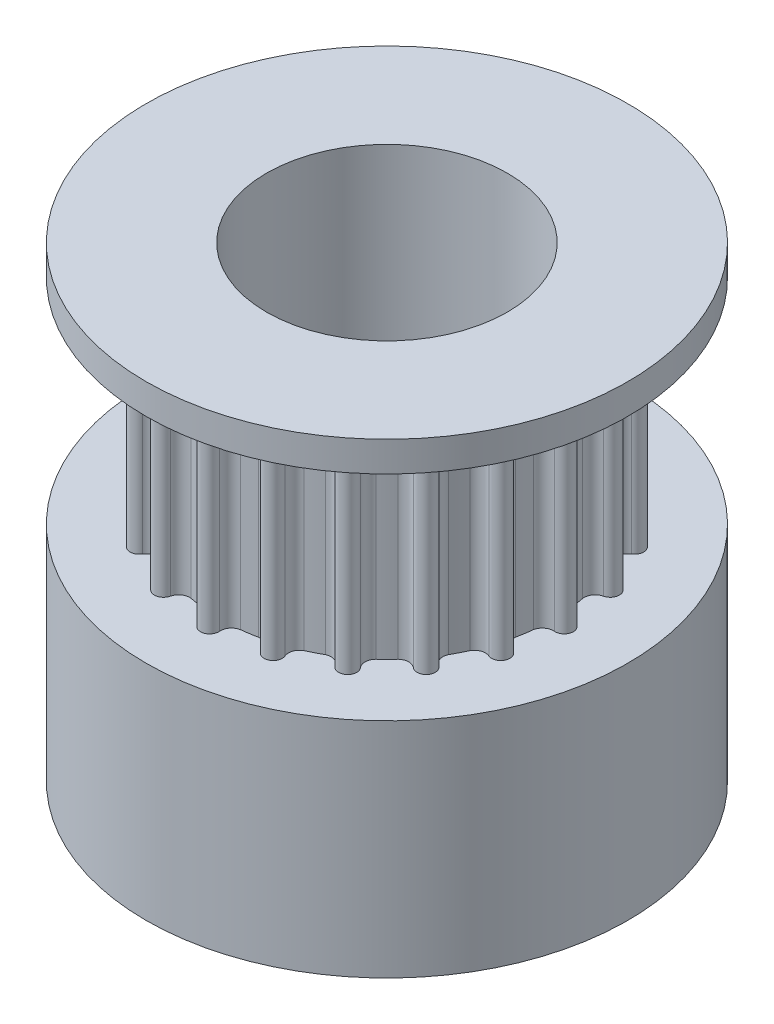
SolidWorks part; units mm, degrees
ref_plane "Front Plane" through (0, 0, 0) normal (0, 0, 1) x (1, 0, 0)
ref_plane "Top Plane" through (0, 0, 0) normal (0, 1, 0) x (1, 0, 0)
ref_plane "Right Plane" through (0, 0, 0) normal (1, 0, 0) x (0, 0, -1)
sketch "Sketch2" plane through (0, 0, 0) normal (0, 1, 0) x (1, 0, 0)
  circle A0 centre (0, 0) radius 8
  circle A1 centre (0, 0) radius 4
  dimension "D1" = 16
  dimension "D2" = 8
extrude "Boss-Extrude1" add sketch "Sketch2" along normal blind 15.5
sketch "Sketch3" plane through (0, 15.5, 0) normal (0, 1, 0) x (1, 0, 0)
  line L0 (0, 0) -> (0, 7.4527) construction
  circle A0 centre (0, 0) radius 8 construction
  circle A1 centre (0, 0) radius 8
  circle A2 centre (0, 0) radius 5.5 construction
  arc A3 (-0.3, 5.8639) -> (0.3, 5.8639) centre (0, 5.8892) cw
  arc A4 (0.3, 5.8639) -> (0.6, 5.4672) centre (0.671, 5.8326) ccw
  arc A5 (-0.3, 5.8639) -> (-0.6, 5.4672) centre (-0.671, 5.8326) cw
  arc A6 (1.1188, 5.385) -> (0.6, 5.4672) centre (0, 0) ccw
  arc A7 (1.5267, 5.6696) -> (2.0974, 5.4842) centre (1.8199, 5.601) cw
  arc A8 (2.0974, 5.4842) -> (2.2601, 5.0142) centre (2.4405, 5.3398) ccw
  arc A9 (1.5267, 5.6696) -> (1.1188, 5.385) centre (1.1643, 5.7545) cw
  arc A10 (2.7281, 4.7757) -> (2.2601, 5.0142) centre (0, 0) ccw
  arc A11 (3.204, 4.9203) -> (3.6894, 4.5677) centre (3.4616, 4.7645) cw
  arc A12 (3.6894, 4.5677) -> (3.6989, 4.0704) centre (3.9711, 4.3243) ccw
  arc A13 (3.204, 4.9203) -> (2.7281, 4.7757) centre (2.8855, 5.1131) cw
  arc A14 (4.0704, 3.6989) -> (3.6989, 4.0704) centre (0, 0) ccw
  arc A15 (4.5677, 3.6894) -> (4.9203, 3.204) centre (4.7645, 3.4616) cw
  arc A16 (4.9203, 3.204) -> (4.7757, 2.7281) centre (5.1131, 2.8855) ccw
  arc A17 (4.5677, 3.6894) -> (4.0704, 3.6989) centre (4.3243, 3.9711) cw
  arc A18 (5.0142, 2.2601) -> (4.7757, 2.7281) centre (0, 0) ccw
  arc A19 (5.4842, 2.0974) -> (5.6696, 1.5267) centre (5.601, 1.8199) cw
  arc A20 (5.6696, 1.5267) -> (5.385, 1.1188) centre (5.7545, 1.1643) ccw
  arc A21 (5.4842, 2.0974) -> (5.0142, 2.2601) centre (5.3398, 2.4405) cw
  arc A22 (5.4672, 0.6) -> (5.385, 1.1188) centre (0, 0) ccw
  arc A23 (5.8639, 0.3) -> (5.8639, -0.3) centre (5.8892, 0) cw
  arc A24 (5.8639, -0.3) -> (5.4672, -0.6) centre (5.8326, -0.671) ccw
  arc A25 (5.8639, 0.3) -> (5.4672, 0.6) centre (5.8326, 0.671) cw
  arc A26 (5.385, -1.1188) -> (5.4672, -0.6) centre (0, 0) ccw
  arc A27 (5.6696, -1.5267) -> (5.4842, -2.0974) centre (5.601, -1.8199) cw
  arc A28 (5.4842, -2.0974) -> (5.0142, -2.2601) centre (5.3398, -2.4405) ccw
  arc A29 (5.6696, -1.5267) -> (5.385, -1.1188) centre (5.7545, -1.1643) cw
  arc A30 (4.7757, -2.7281) -> (5.0142, -2.2601) centre (0, 0) ccw
  arc A31 (4.9203, -3.204) -> (4.5677, -3.6894) centre (4.7645, -3.4616) cw
  arc A32 (4.5677, -3.6894) -> (4.0704, -3.6989) centre (4.3243, -3.9711) ccw
  arc A33 (4.9203, -3.204) -> (4.7757, -2.7281) centre (5.1131, -2.8855) cw
  arc A34 (3.6989, -4.0704) -> (4.0704, -3.6989) centre (0, 0) ccw
  arc A35 (3.6894, -4.5677) -> (3.204, -4.9203) centre (3.4616, -4.7645) cw
  arc A36 (3.204, -4.9203) -> (2.7281, -4.7757) centre (2.8855, -5.1131) ccw
  arc A37 (3.6894, -4.5677) -> (3.6989, -4.0704) centre (3.9711, -4.3243) cw
  arc A38 (2.2601, -5.0142) -> (2.7281, -4.7757) centre (0, 0) ccw
  arc A39 (2.0974, -5.4842) -> (1.5267, -5.6696) centre (1.8199, -5.601) cw
  arc A40 (1.5267, -5.6696) -> (1.1188, -5.385) centre (1.1643, -5.7545) ccw
  arc A41 (2.0974, -5.4842) -> (2.2601, -5.0142) centre (2.4405, -5.3398) cw
  arc A42 (0.6, -5.4672) -> (1.1188, -5.385) centre (0, 0) ccw
  arc A43 (0.3, -5.8639) -> (-0.3, -5.8639) centre (0, -5.8892) cw
  arc A44 (-0.3, -5.8639) -> (-0.6, -5.4672) centre (-0.671, -5.8326) ccw
  arc A45 (0.3, -5.8639) -> (0.6, -5.4672) centre (0.671, -5.8326) cw
  arc A46 (-1.1188, -5.385) -> (-0.6, -5.4672) centre (0, 0) ccw
  arc A47 (-1.5267, -5.6696) -> (-2.0974, -5.4842) centre (-1.8199, -5.601) cw
  arc A48 (-2.0974, -5.4842) -> (-2.2601, -5.0142) centre (-2.4405, -5.3398) ccw
  arc A49 (-1.5267, -5.6696) -> (-1.1188, -5.385) centre (-1.1643, -5.7545) cw
  arc A50 (-2.7281, -4.7757) -> (-2.2601, -5.0142) centre (0, 0) ccw
  arc A51 (-3.204, -4.9203) -> (-3.6894, -4.5677) centre (-3.4616, -4.7645) cw
  arc A52 (-3.6894, -4.5677) -> (-3.6989, -4.0704) centre (-3.9711, -4.3243) ccw
  arc A53 (-3.204, -4.9203) -> (-2.7281, -4.7757) centre (-2.8855, -5.1131) cw
  arc A54 (-4.0704, -3.6989) -> (-3.6989, -4.0704) centre (0, 0) ccw
  arc A55 (-4.5677, -3.6894) -> (-4.9203, -3.204) centre (-4.7645, -3.4616) cw
  arc A56 (-4.9203, -3.204) -> (-4.7757, -2.7281) centre (-5.1131, -2.8855) ccw
  arc A57 (-4.5677, -3.6894) -> (-4.0704, -3.6989) centre (-4.3243, -3.9711) cw
  arc A58 (-5.0142, -2.2601) -> (-4.7757, -2.7281) centre (0, 0) ccw
  arc A59 (-5.4842, -2.0974) -> (-5.6696, -1.5267) centre (-5.601, -1.8199) cw
  arc A60 (-5.6696, -1.5267) -> (-5.385, -1.1188) centre (-5.7545, -1.1643) ccw
  arc A61 (-5.4842, -2.0974) -> (-5.0142, -2.2601) centre (-5.3398, -2.4405) cw
  arc A62 (-5.4672, -0.6) -> (-5.385, -1.1188) centre (0, 0) ccw
  arc A63 (-5.8639, -0.3) -> (-5.8639, 0.3) centre (-5.8892, 0) cw
  arc A64 (-5.8639, 0.3) -> (-5.4672, 0.6) centre (-5.8326, 0.671) ccw
  arc A65 (-5.8639, -0.3) -> (-5.4672, -0.6) centre (-5.8326, -0.671) cw
  arc A66 (-5.385, 1.1188) -> (-5.4672, 0.6) centre (0, 0) ccw
  arc A67 (-5.6696, 1.5267) -> (-5.4842, 2.0974) centre (-5.601, 1.8199) cw
  arc A68 (-5.4842, 2.0974) -> (-5.0142, 2.2601) centre (-5.3398, 2.4405) ccw
  arc A69 (-5.6696, 1.5267) -> (-5.385, 1.1188) centre (-5.7545, 1.1643) cw
  arc A70 (-4.7757, 2.7281) -> (-5.0142, 2.2601) centre (0, 0) ccw
  arc A71 (-4.9203, 3.204) -> (-4.5677, 3.6894) centre (-4.7645, 3.4616) cw
  arc A72 (-4.5677, 3.6894) -> (-4.0704, 3.6989) centre (-4.3243, 3.9711) ccw
  arc A73 (-4.9203, 3.204) -> (-4.7757, 2.7281) centre (-5.1131, 2.8855) cw
  arc A74 (-3.6989, 4.0704) -> (-4.0704, 3.6989) centre (0, 0) ccw
  arc A75 (-3.6894, 4.5677) -> (-3.204, 4.9203) centre (-3.4616, 4.7645) cw
  arc A76 (-3.204, 4.9203) -> (-2.7281, 4.7757) centre (-2.8855, 5.1131) ccw
  arc A77 (-3.6894, 4.5677) -> (-3.6989, 4.0704) centre (-3.9711, 4.3243) cw
  arc A78 (-2.2601, 5.0142) -> (-2.7281, 4.7757) centre (0, 0) ccw
  arc A79 (-2.0974, 5.4842) -> (-1.5267, 5.6696) centre (-1.8199, 5.601) cw
  arc A80 (-1.5267, 5.6696) -> (-1.1188, 5.385) centre (-1.1643, 5.7545) ccw
  arc A81 (-2.0974, 5.4842) -> (-2.2601, 5.0142) centre (-2.4405, 5.3398) cw
  arc A82 (-0.6, 5.4672) -> (-1.1188, 5.385) centre (0, 0) ccw
  point P14 (1.0917, 5.385)
  point P169 (0, 0)
  dimension "D1" = 11
  dimension "D2" = 0.3
  dimension "D3" = 0.3
  dimension "D4" = 20
extrude "Cut-Extrude1" cut sketch "Sketch3" against normal blind 7.1 from offset 1 offset against normal yes
sketch "Sketch4" plane through (0, 0, 0) normal (0, 0, 1) x (1, 0, 0)
  circle A0 centre (0, 3.75) radius 2
  dimension "D1" = 4
  dimension "D2" = 3.75
extrude "Cut-Extrude2" cut sketch "Sketch4" against normal up to next
sketch "Sketch5" plane through (0, 0, 0) normal (1, 0, 0) x (0, 0, -1)
  circle A0 centre (0, 3.75) radius 2
  dimension "D1" = 4
  dimension "D2" = 3.75
extrude "Cut-Extrude3" cut sketch "Sketch5" against normal up to next
